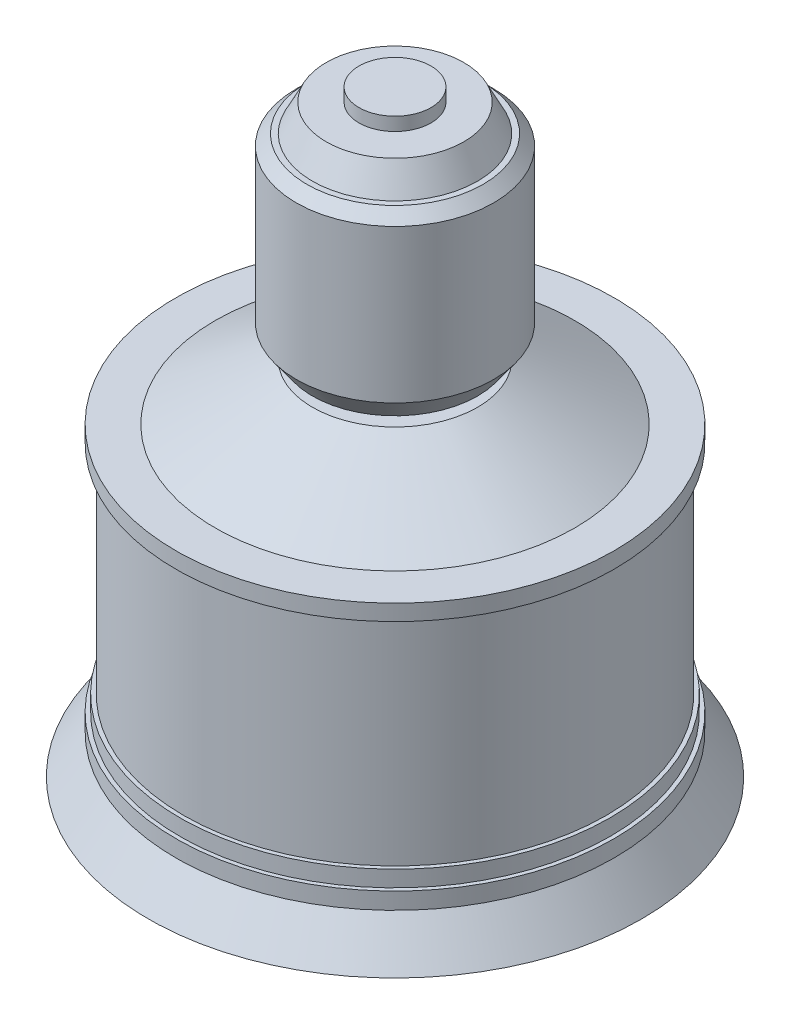
SolidWorks part; units mm, degrees
ref_plane "前视基准面" through (0, 0, 0) normal (0, 0, 1) x (1, 0, 0)
ref_plane "上视基准面" through (0, 0, 0) normal (0, 1, 0) x (1, 0, 0)
ref_plane "右视基准面" through (0, 0, 0) normal (1, 0, 0) x (0, 0, -1)
sketch "草图1" plane through (0, 0, 0) normal (0, 0, 1) x (1, 0, 0)
  line L0 (-153.8106, 41.5442) -> (-188.8106, -8.5579)
  line L1 (-153.8106, 381.4421) -> (406.1894, 381.4421)
  line L2 (-153.8106, 381.4421) -> (-153.8106, 361.0116)
  line L3 (-153.8106, 41.5442) -> (406.1894, 41.5442)
  line L4 (406.1894, 381.4421) -> (406.1894, 361.0116)
  line L5 (406.1894, 41.5442) -> (441.1894, -8.5579)
  line L6 (-188.8106, -8.5579) -> (441.1894, -8.5579)
  line L7 (-153.8106, 361.0116) -> (-143.8106, 361.0116)
  line L8 (-143.8106, 361.0116) -> (-143.8106, 83.5795)
  line L9 (-143.8106, 62.9113) -> (-153.8106, 62.9113)
  line L10 (406.1894, 361.0116) -> (396.1894, 361.0116)
  line L11 (396.1894, 361.0116) -> (396.1894, 83.5795)
  line L12 (396.1894, 64.8772) -> (406.1894, 64.8772)
  line L13 (-153.8106, 62.9113) -> (-153.8106, 41.5442)
  line L14 (406.1894, 64.8772) -> (406.1894, 41.5442)
  line L15 (126.1894, 41.5442) -> (126.1894, 754.802)
  line L16 (396.1894, 83.5795) -> (401.1894, 83.5795)
  line L17 (-103.4717, 381.4421) -> (20.6832, 452.9095)
  line L18 (20.6832, 452.9095) -> (71.652, 452.9095)
  line L19 (71.652, 452.9095) -> (71.652, 465.325)
  line L20 (71.652, 465.325) -> (20.6832, 465.325)
  line L21 (20.6832, 465.325) -> (0, 494.0767)
  line L22 (0, 494.0767) -> (0, 514.987)
  line L23 (0, 514.987) -> (0, 689.4573)
  line L24 (0, 689.4573) -> (13.6088, 703.0661)
  line L25 (13.6088, 703.0661) -> (20.6832, 703.0661)
  line L26 (20.6832, 703.0661) -> (38.3262, 737.8124)
  line L27 (38.3262, 737.8124) -> (80.1468, 737.8124)
  line L28 (80.1468, 737.8124) -> (80.1468, 754.802)
  line L29 (80.1468, 754.802) -> (172.232, 754.802)
  line L30 (126.1894, 41.5442) -> (126.1894, -8.5579)
  line L31 (355.8506, 381.4421) -> (231.6957, 452.9095)
  line L32 (172.232, 737.8124) -> (172.232, 754.802)
  line L33 (214.0526, 737.8124) -> (172.232, 737.8124)
  line L34 (231.6957, 703.0661) -> (214.0526, 737.8124)
  line L35 (238.77, 703.0661) -> (231.6957, 703.0661)
  line L36 (252.3789, 689.4573) -> (238.77, 703.0661)
  line L37 (252.3789, 514.987) -> (252.3789, 689.4573)
  line L38 (252.3789, 494.0767) -> (252.3789, 514.987)
  line L39 (231.6957, 465.325) -> (252.3789, 494.0767)
  line L40 (180.7268, 465.325) -> (231.6957, 465.325)
  line L41 (180.7268, 452.9095) -> (180.7268, 465.325)
  line L42 (231.6957, 452.9095) -> (180.7268, 452.9095)
  line L43 (-143.8106, 62.9113) -> (396.1894, 64.8772)
  line L44 (396.1894, 83.5795) -> (-143.8106, 83.5795)
  line L45 (401.1894, 83.5795) -> (401.1894, 64.8772)
  line L46 (-148.8106, 62.9113) -> (-148.8106, 83.5795)
  line L47 (-148.8106, 83.5795) -> (-143.8106, 83.5795)
  point P38 (126.1894, 754.802)
  dimension "D1" = 10
  dimension "D2" = 10
  dimension "D3" = 540
  dimension "D4" = 630
  dimension "D5" = 390
revolve "旋转6" add sketch "草图1" angle 360 about L15
sketch "草图2" plane through (0, 0, 0) normal (0, 0, 1) x (1, 0, 0)
  line L0 (-176.2735, -8.5579) -> (-140.1485, 41.5442)
  line L1 (-188.8106, -8.5579) -> (441.1894, -8.5579) construction
  line L2 (406.1894, 41.5442) -> (-153.8106, 41.5442) construction
  line L3 (-140.1485, 41.5442) -> (-140.1485, 56.1395)
  line L4 (-140.1485, 56.1395) -> (-131.6817, 56.1395)
  line L5 (-131.6817, 56.1395) -> (-131.6817, 76.7421)
  line L6 (-131.6817, 76.7421) -> (-121.8037, 76.7421)
  line L7 (-121.8037, 76.7421) -> (-121.8037, 364.3058)
  line L8 (126.1894, 364.3058) -> (126.1894, -8.5579)
  line L10 (-121.8037, 364.3058) -> (126.1894, 364.3058)
  line L11 (126.1894, -8.5579) -> (-176.2735, -8.5579)
revolve "切除-旋转1" cut sketch "草图2" angle 360 about L8
scale "缩放比例1" scale about centroid uniform scaling yes scale factor 0.1
